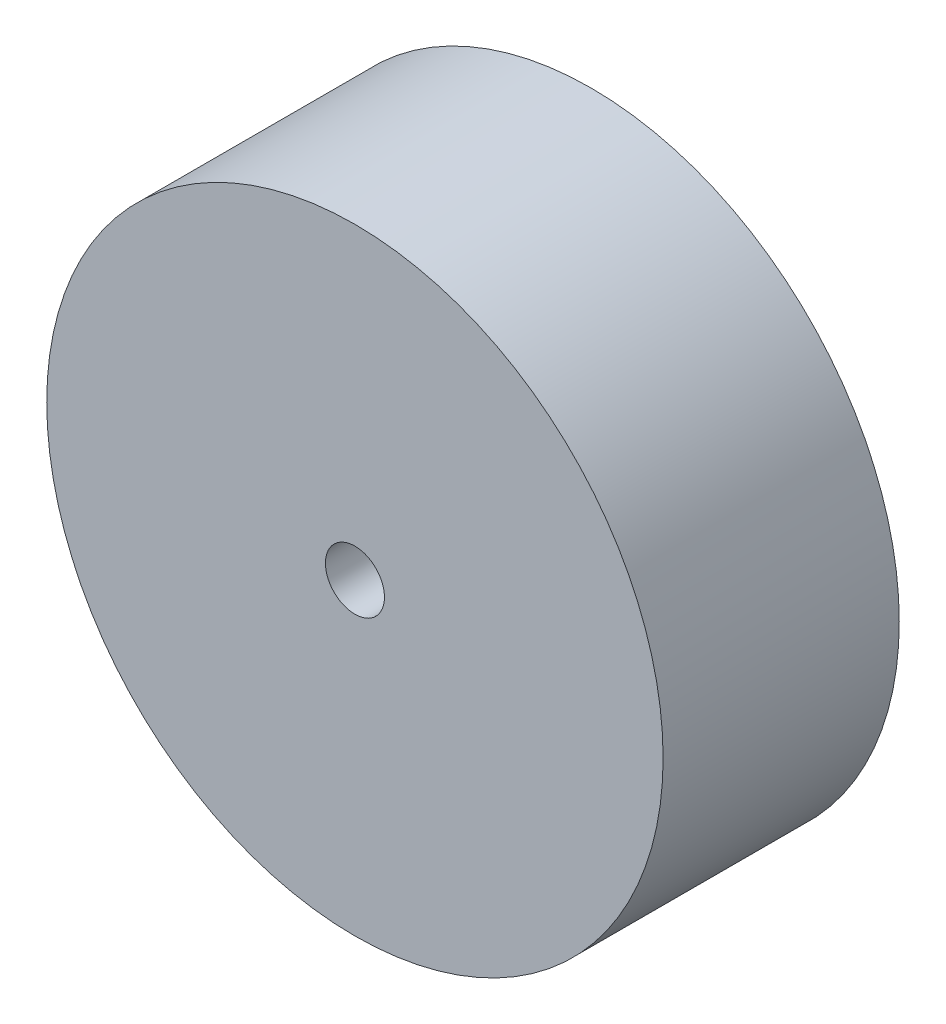
SolidWorks part; units mm, degrees
ref_plane "Front Plane" through (0, 0, 0) normal (0, 0, 1) x (1, 0, 0)
ref_plane "Top Plane" through (0, 0, 0) normal (0, 1, 0) x (1, 0, 0)
ref_plane "Right Plane" through (0, 0, 0) normal (1, 0, 0) x (0, 0, -1)
sketch "Sketch1" plane through (0, 0, 0) normal (0, 0, 1) x (1, 0, 0)
  circle A0 centre (0, 0) radius 33.1493
extrude "Boss-Extrude1" add sketch "Sketch1" along normal blind 25.4
hole_wizard "1/4 (0.25) Diameter Hole1" positions "Sketch2" profile "Sketch3" hole size "1/4" standard "ANSI Inch" end condition through all
sketch "Sketch2" plane through (0, 0, 25.4) normal (0, 0, 1) x (1, 0, 0)
  point P0 (0, 0)
sketch "Sketch3" plane through (0, 0, 25.4) normal (1, 0, 0) x (0, -1, 0)
  line L0 (0, 0) -> (0, 25.4)
  line L1 (0, 25.4) -> (3.175, 25.4)
  line L2 (3.175, 25.4) -> (3.175, 0)
  line L5 (3.175, 0) -> (0, 0)
  line L11 (0, -6.35) -> (0, 107.95) construction
  dimension "Thru Hole Dia." = 6.35
  dimension "Thru Hole Depth" = 25.4
